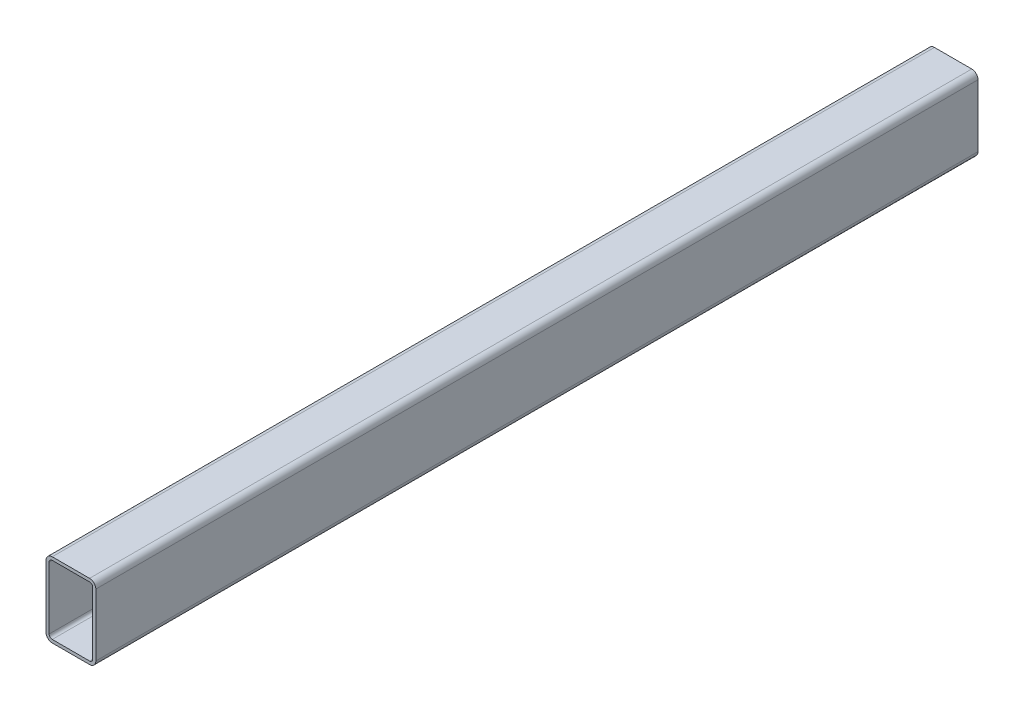
SolidWorks part; units mm, degrees
ref_plane "Front Plane" through (0, 0, 0) normal (0, 0, 1) x (1, 0, 0)
ref_plane "Top Plane" through (0, 0, 0) normal (0, 1, 0) x (1, 0, 0)
ref_plane "Right Plane" through (0, 0, 0) normal (1, 0, 0) x (0, 0, -1)
sketch "Sketch1" plane through (0, 0, 0) normal (0, 0, 1) x (1, 0, 0)
  line L0 (19.4, 34.925) -> (-19.4, 34.925)
  line L1 (19.4, -38.1) -> (-19.4, -38.1)
  line L2 (25.4, -32.1) -> (25.4, 32.1)
  line L3 (19.4, 38.1) -> (-19.4, 38.1)
  line L4 (-25.4, -32.1) -> (-25.4, 32.1)
  line L5 (25.4, -38.1) -> (-25.4, 38.1) construction
  line L6 (25.4, 38.1) -> (-25.4, -38.1) construction
  line L7 (-22.225, -32.1) -> (-22.225, 32.1)
  line L8 (19.4, -34.925) -> (-19.4, -34.925)
  line L9 (22.225, -32.1) -> (22.225, 32.1)
  arc A0 (-19.4, -38.1) -> (-25.4, -32.1) centre (-19.4, -32.1) cw
  arc A1 (19.4, -38.1) -> (25.4, -32.1) centre (19.4, -32.1) ccw
  arc A2 (25.4, 32.1) -> (19.4, 38.1) centre (19.4, 32.1) ccw
  arc A3 (-19.4, 38.1) -> (-25.4, 32.1) centre (-19.4, 32.1) ccw
  arc A4 (-19.4, 34.925) -> (-22.225, 32.1) centre (-19.4, 32.1) ccw
  arc A5 (-19.4, -34.925) -> (-22.225, -32.1) centre (-19.4, -32.1) cw
  arc A6 (19.4, -34.925) -> (22.225, -32.1) centre (19.4, -32.1) ccw
  arc A7 (22.225, 32.1) -> (19.4, 34.925) centre (19.4, 32.1) ccw
  point P0 (0, 0)
  dimension "D1" = 6
  dimension "D3" = 76.2
  dimension "D4" = 50.8
  dimension "D2" = 3.175
extrude "Boss-Extrude1" [suppressed] add sketch "Sketch1" along normal mid plane 900
sketch "Sketch2" plane through (0, 0, 0) normal (1, 0, 0) x (0, 0, -1)
  line L0 (-450, 0) -> (450, 0)
  dimension "D1" = 900
other "Cnc 3X2X0.125(1)"
ref_plane "Plane1" through (0, 0, 450) normal (0, 0, -1) x (0, 1, 0)
sketch "Sketch11" plane through (0, 0, 450) normal (0, 0, -1) x (0, 1, 0)
  line L0 (31.75, 22.225) -> (-31.75, 22.225)
  line L1 (31.75, -25.4) -> (-31.75, -25.4)
  line L2 (38.1, -19.05) -> (38.1, 19.05)
  line L3 (31.75, 25.4) -> (-31.75, 25.4)
  line L4 (-38.1, -19.05) -> (-38.1, 19.05)
  line L5 (38.1, -25.4) -> (-38.1, 25.4) construction
  line L6 (38.1, 25.4) -> (-38.1, -25.4) construction
  line L7 (-34.925, -19.05) -> (-34.925, 19.05)
  line L8 (31.75, -22.225) -> (-31.75, -22.225)
  line L9 (34.925, -19.05) -> (34.925, 19.05)
  line L10 (38.1, -25.4) -> (-38.1, -25.4) construction
  line L11 (-38.1, -25.4) -> (-38.1, 25.4) construction
  line L12 (38.1, -25.4) -> (38.1, 25.4) construction
  line L13 (38.1, 25.4) -> (-38.1, 25.4) construction
  line L14 (-34.925, -22.225) -> (-34.925, 22.225) construction
  line L15 (34.925, -22.225) -> (-34.925, -22.225) construction
  line L16 (34.925, -22.225) -> (34.925, 22.225) construction
  line L17 (34.925, 22.225) -> (-34.925, 22.225) construction
  arc A0 (-31.75, -25.4) -> (-38.1, -19.05) centre (-31.75, -19.05) cw
  arc A1 (31.75, -25.4) -> (38.1, -19.05) centre (31.75, -19.05) ccw
  arc A2 (38.1, 19.05) -> (31.75, 25.4) centre (31.75, 19.05) ccw
  arc A3 (-31.75, 25.4) -> (-38.1, 19.05) centre (-31.75, 19.05) ccw
  arc A4 (-34.925, -19.05) -> (-31.75, -22.225) centre (-31.75, -19.05) ccw
  arc A5 (31.75, -22.225) -> (34.925, -19.05) centre (31.75, -19.05) ccw
  arc A6 (31.75, 22.225) -> (34.925, 19.05) centre (31.75, 19.05) cw
  arc A7 (-31.75, 22.225) -> (-34.925, 19.05) centre (-31.75, 19.05) ccw
  point P0 (0, 0)
  point P34 (0, 0)
  dimension "D4" = 6.35
  dimension "D5" = 3.175
  dimension "D1" = 76.2
  dimension "D2" = 50.8
  dimension "D3" = 3.175
equation "\"M5_tap\"=4.2mm\t\t\t\t\t\t\t' Below you can do mesurements as follows: cm, mm, ft, in, m, "
equation "\"M5_clearence\"=5.5mm"
equation "\"M6_tap\"=5mm"
equation "\"M6_clearence\"=6.6mm"
equation "\"work_area_width\"=1100mm"
equation "\"work_area_depth\"=900mm"
equation "\"D3@Sketch1\"=\"steel_sides_width\""
equation "\"D4@Sketch1\"=\"steel_sides_height\""
equation "\"D1@Sketch1\"=\"steel_sides_radius\""
equation "\"D2@Sketch1\"=\"steel_sides_wall_thickness\""
equation "\"D1@Boss-Extrude1\"=\"work_area_depth\""
equation "\"steel_base_width\"=3in\t"
equation "\"steel_base_height\"=2in"
equation "\"steel_base_wall_thickness\"=0.125in"
equation "\"steel_base_radius\"=6mm"
equation "\"steel_sides_width\"=3in\t\t\t\t\t'this tube is rotated so flip width/height"
equation "\"steel_sides_height\"=2in\t\t\t\t'this tube is rotated so flip width/height"
equation "\"steel_sides_wall_thickness\"=0.125in"
equation "\"steel_sides_radius\"=6mm"
equation "\"steel_gantry_width\"=4in\t\t\t\t'this tube is rotated so flip width/height"
equation "\"steel_gantry_height\"=3in\t\t\t\t'this tube is rotated so flip width/height"
equation "\"steel_gantry_wall_thickness\"=0.125in"
equation "\"steel_gantry_radius\"=6mm"
equation "\"steel_rollers_width\"=3in"
equation "\"steel_rollers_height\"=2in\t\t\t\t'keep as low as possible as this increases how big plastic parts are"
equation "\"steel_rollers_wall_thickness\"=0.125in"
equation "\"steel_rollers_radius\"=6mm"
equation "\"steel_zbox_width\"=4in\t\t\t\t\t'if the gantry height (rotated) is too thick, a wider zbox is necessary"
equation "\"steel_zbox_height\"=2in\t\t\t\t\t'hole patteren changes as the zbox and gantry height (rotated) changes."
equation "\"steel_zbox_wall_thickness\"=0.125in"
equation "\"steel_zbox_radius\"=6mm"
equation "\"alu_zangle_width\"=3.5in\t\t\t\t\t'check that it doesn't interfer with the gantry"
equation "\"alu_zangle_height\"=2in"
equation "\"alu_zangle_wall_thickness\"=0.25in\t\t\t'check that it doesn't interfer with the gantry"
equation "\"D1@Sketch2\"=\"work_area_depth\""
equation "\"D2@Sketch11\"=\"profile_heigth\""
equation "\"D1@Sketch11\"=\"profile_width\""
equation "\"D3@Sketch11\"=\"profile_wall\""
equation "\"D5@Sketch11\"=\"profile_wall\""
equation "\"D4@Sketch11\"=\"profile_wall\"*2"
